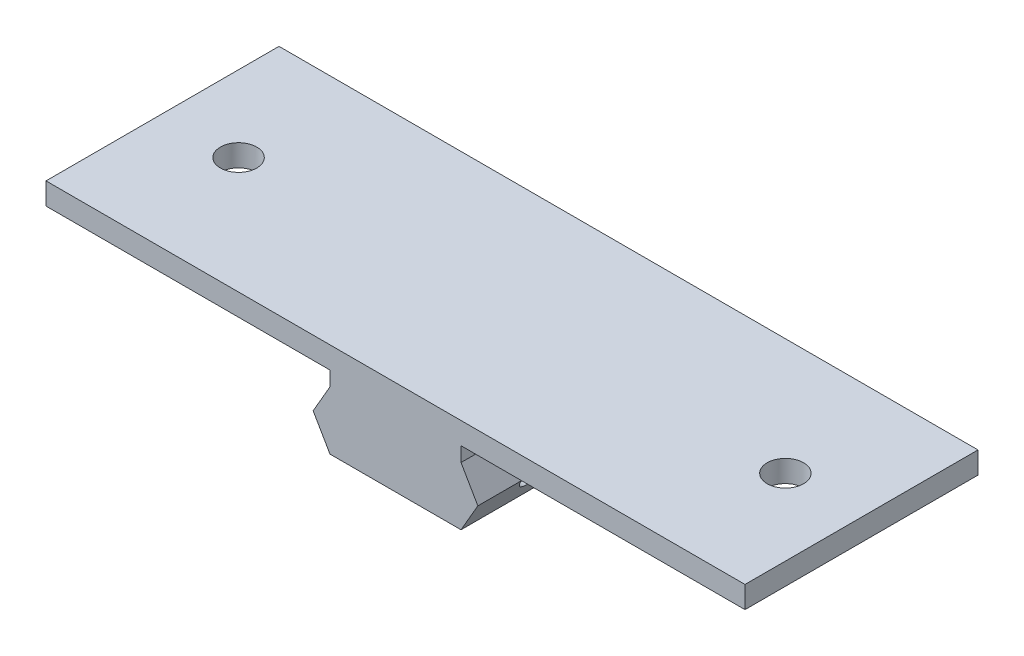
SolidWorks part; units mm, degrees
ref_plane "Front Plane" through (0, 0, 0) normal (0, 0, 1) x (1, 0, 0)
ref_plane "Top Plane" through (0, 0, 0) normal (0, 1, 0) x (1, 0, 0)
ref_plane "Right Plane" through (0, 0, 0) normal (1, 0, 0) x (0, 0, -1)
sketch "Sketch1" plane through (0, 0, 0) normal (0, 0, 1) x (1, 0, 0)
  line L0 (9, 0) -> (-9, 0)
  line L1 (-9, 0) -> (-11.3094, 4)
  line L2 (-11.3094, 4) -> (-9, 8)
  line L3 (-9, 8) -> (9, 8)
  line L4 (9, 8) -> (11.3094, 4)
  line L5 (11.3094, 4) -> (9, 0)
  dimension "D1" = 18
  dimension "D2" = 120
  dimension "D3" = 120
  dimension "D4" = 120
  dimension "D5" = 120
  dimension "D6" = 8
extrude "Boss-Extrude1" add sketch "Sketch1" along normal blind 32
sketch "Sketch2" plane through (0, 0, 0) normal (1, 0, 0) x (0, 0, -1)
  line L0 (-32, 4) -> (0, 4) construction
  line L1 (-32, 4) -> (-32, 8) construction
  circle A0 centre (-24, 4) radius 2
  dimension "D1" = 4
  dimension "D2" = 8
extrude "Cut-Extrude1" cut sketch "Sketch2" against normal through all both and the other way through all contours A0
pattern_linear "LPattern1" count 3 spacing 8 along (0, 0, -1) of "Cut-Extrude1"
sketch "Sketch3" plane through (0, 0, 0) normal (1, 0, 0) x (0, 0, -1)
  line L1 (-32, 8) -> (0, 8)
  line L2 (-32, 8) -> (-32, 10)
  line L3 (-32, 10) -> (0, 10)
  line L4 (0, 8) -> (0, 10)
  line L5 (-32, 8) -> (0, 10) construction
  line L6 (-32, 10) -> (0, 8) construction
  point P4 (-16, 9)
  dimension "D1" = 2
extrude "Boss-Extrude2" add sketch "Sketch3" along normal up to vertex (9 mm away) and the other way up to vertex (9 mm away) up to point (9, 8, 32) other way up to point (-9, 8, 32)
sketch "Sketch4" plane through (0, 0, 0) normal (1, 0, 0) x (0, 0, -1)
  line L1 (-32, 10) -> (0, 10)
  line L2 (-32, 10) -> (-32, 13)
  line L3 (-32, 13) -> (0, 13)
  line L4 (0, 10) -> (0, 13)
  line L5 (-32, 10) -> (0, 13) construction
  line L6 (-32, 13) -> (0, 10) construction
  point P4 (-16, 11.5)
  dimension "D1" = 3
extrude "Boss-Extrude3" add sketch "Sketch4" along normal blind 48 and the other way blind 48
sketch "Sketch5" plane through (0, 13, 0) normal (0, 1, 0) x (1, 0, 0)
  line L0 (0, -16) -> (37.55, -16) construction
  line L1 (-37.55, -16) -> (0, -16) construction
  line L3 (0, 0) -> (0, -32) construction
  line L6 (-48, -32) -> (48, -32) construction
  circle A0 centre (-37.55, -16) radius 2.5
  circle A1 centre (37.55, -16) radius 2.5
  dimension "D3" = 5
  dimension "D1" = 37.55
extrude "Cut-Extrude2" cut sketch "Sketch5" against normal blind 10
